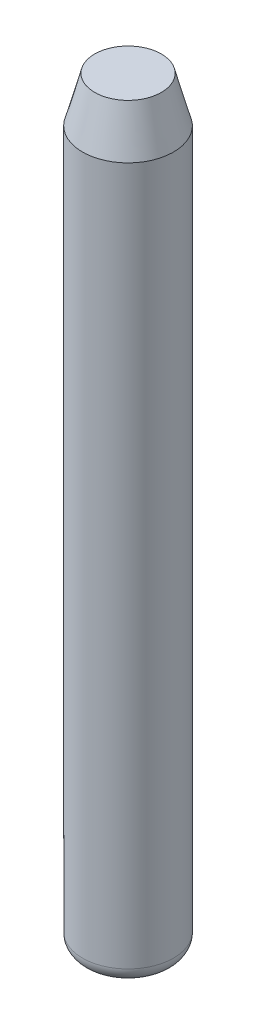
SolidWorks part; units mm, degrees
ref_plane "Front Plane" through (0, 0, 0) normal (0, 0, 1) x (1, 0, 0)
ref_plane "Top Plane" through (0, 0, 0) normal (0, 1, 0) x (1, 0, 0)
ref_plane "Right Plane" through (0, 0, 0) normal (1, 0, 0) x (0, 0, -1)
sketch "Sketch1" plane through (0, 0, 0) normal (0, 1, 0) x (1, 0, 0)
  circle A0 centre (0, 0) radius 1.5
  dimension "D1" = 3
extrude "Boss-Extrude1" add sketch "Sketch1" along normal blind 25
chamfer "Chamfer1" distance 1.5 angle 15 1 edges at (0, 25, 1.5)
fillet "Fillet1" radius 0.5 1 edges at (0, 0, 1.5)
